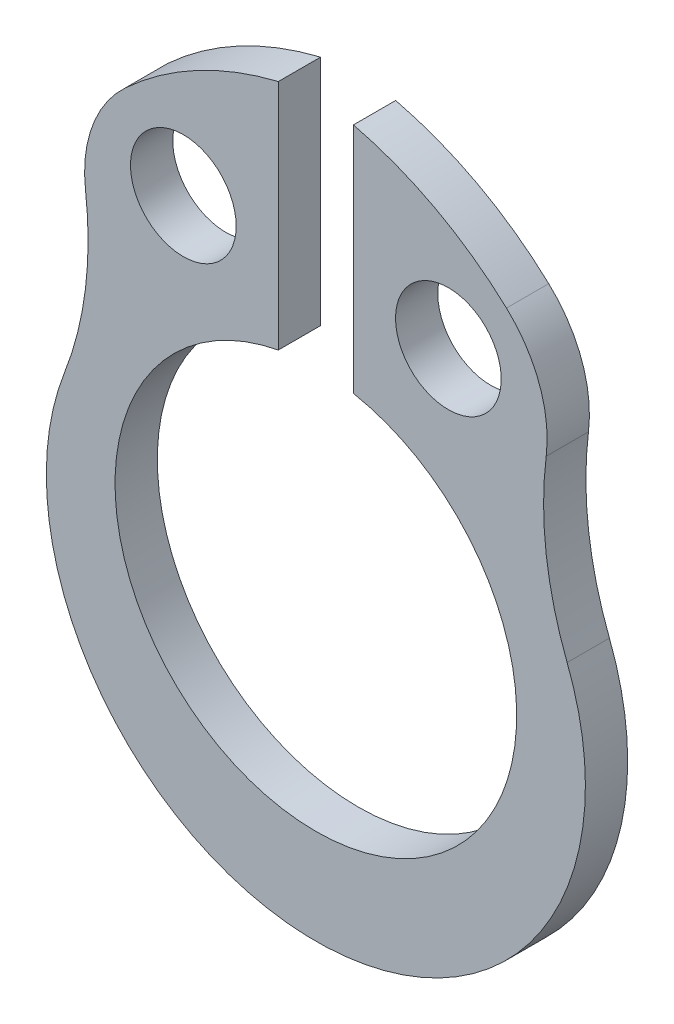
SolidWorks part; units mm, degrees
ref_plane "Front Plane" through (0, 0, 0) normal (0, 0, 1) x (1, 0, 0)
ref_plane "Top Plane" through (0, 0, 0) normal (0, 1, 0) x (1, 0, 0)
ref_plane "Right Plane" through (0, 0, 0) normal (1, 0, 0) x (0, 0, -1)
sketch "Sketch1" plane through (0, 0, 0) normal (0, 0, 1) x (1, 0, 0)
  line L0 (0, -1000) -> (0, 49000) construction
  line L1 (-1000, 0) -> (49000, 0) construction
  line L2 (0.3552, 4.0665) -> (0.3552, 1.8665)
  line L3 (0, 4.0665) -> (0.3552, 4.0665) construction
  line L4 (-0.3552, 4.0665) -> (-0.3552, 1.8665)
  circle A0 centre (0, 0) radius 1.9 construction
  circle A1 centre (0, 0) radius 2.8 construction
  circle A5 centre (0, -0.25) radius 2.55 construction
  arc A6 (-2.3772, 0.6726) -> (2.3772, 0.6726) centre (0, -0.25) ccw
  circle A8 centre (-1.2537, 2.6822) radius 0.5
  circle A12 centre (1.2537, 2.6822) radius 0.5
  arc A13 (-0.3552, 4.0665) -> (-1.8034, 3.2898) centre (0.4146, 0.8928) ccw
  arc A14 (-1.8034, 3.2898) -> (-2.1791, 2.2634) centre (-0.9891, 2.4097) ccw
  arc A15 (-2.1791, 2.2634) -> (-2.3772, 0.6726) centre (-5.4421, 1.8621) cw
  arc A16 (2.1791, 2.2634) -> (2.3772, 0.6726) centre (5.4421, 1.8621) ccw
  arc A17 (1.8034, 3.2898) -> (2.1791, 2.2634) centre (0.9891, 2.4097) cw
  arc A18 (0.3552, 4.0665) -> (1.8034, 3.2898) centre (-0.4146, 0.8928) cw
  arc A19 (-0.3552, 1.8665) -> (0.3552, 1.8665) centre (0, 0) ccw
  point P5 (0, -1.9)
  point P6 (0, -2.8)
  point P19 (0, 4.0665)
  point P20 (-1.0838, 3.2465)
  point P26 (-1.0063, 2.816)
  point P27 (-2.0238, 2.4179)
  point P31 (-1.5814, 3.4575)
  point P32 (-1.1169, 2.8271)
  point P33 (-1.9464, 3.2695)
  point P42 (-2.2118, 2.4732)
  point P43 (-1.2718, 2.7276)
  point P44 (0, 0)
  point P45 (-1.2406, 2.7523)
  point P46 (-1.8034, 3.2898)
  point P47 (-1.2532, 2.6195)
  point P48 (-1.2537, 2.6822)
  dimension "D1" = 3.8
  dimension "D2" = 0.25
  dimension "D3" = 0.9
  dimension "D5" = 1
  dimension "D4" = 2.2
extrude "Boss-Extrude1" add sketch "Sketch1" along normal mid plane 0.4
